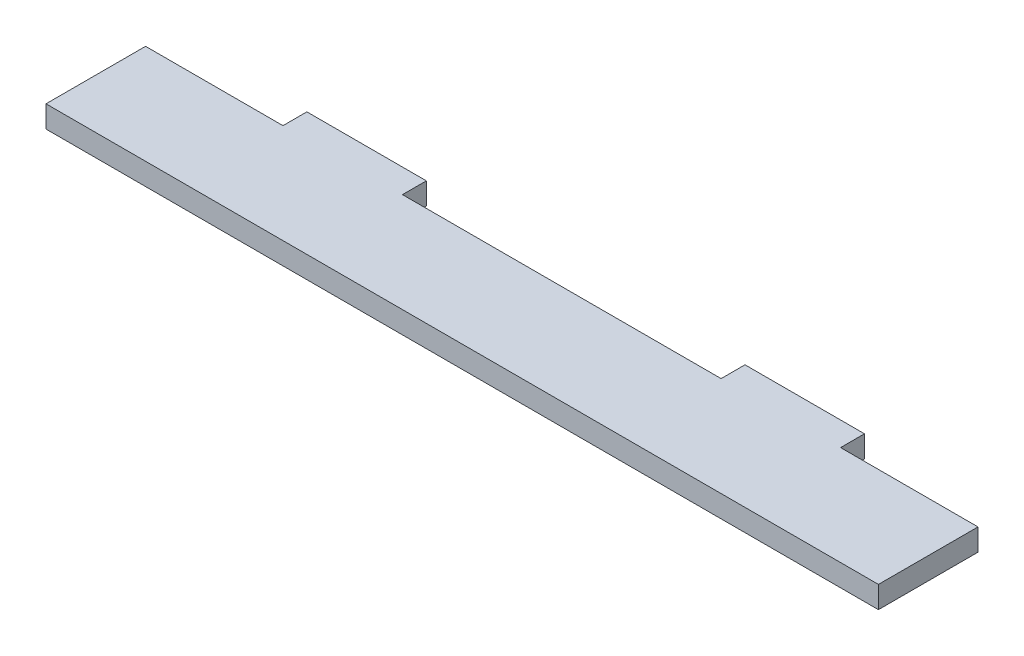
SolidWorks part; units mm, degrees
ref_plane "Front Plane" through (0, 0, 0) normal (0, 0, 1) x (1, 0, 0)
ref_plane "Top Plane" through (0, 0, 0) normal (0, 1, 0) x (1, 0, 0)
ref_plane "Right Plane" through (0, 0, 0) normal (1, 0, 0) x (0, 0, -1)
sketch "Sketch1" plane through (0, 0, 0) normal (0, 1, 0) x (1, 0, 0)
  line L0 (0, -55) -> (0, 55) construction
  line L1 (-104.5, -12.5) -> (104.5, -12.5)
  line L2 (-104.5, -12.5) -> (-104.5, 12.5)
  line L3 (-104.5, 12.5) -> (104.5, 12.5)
  line L4 (104.5, -12.5) -> (104.5, 12.5)
  line L5 (-104.5, -12.5) -> (104.5, 12.5) construction
  line L6 (-104.5, 12.5) -> (104.5, -12.5) construction
  line L7 (-70, 12.5) -> (-40, 12.5)
  line L8 (-70, 12.5) -> (-70, 18.5)
  line L9 (-70, 18.5) -> (-40, 18.5)
  line L10 (-40, 12.5) -> (-40, 18.5)
  line L11 (40, 12.5) -> (40, 18.5)
  line L12 (70, 12.5) -> (70, 18.5)
  line L13 (70, 18.5) -> (40, 18.5)
  point P0 (0, 0)
  dimension "D1" = 25
  dimension "D2" = 209
  dimension "D3" = 40
  dimension "D4" = 6
  dimension "D5" = 30
extrude "Boss-Extrude1" add sketch "Sketch1" along normal blind 5.5 contours L3 L10 L9 L8 | L1 L4 L3 L2 | L12 L13 L11 L3
